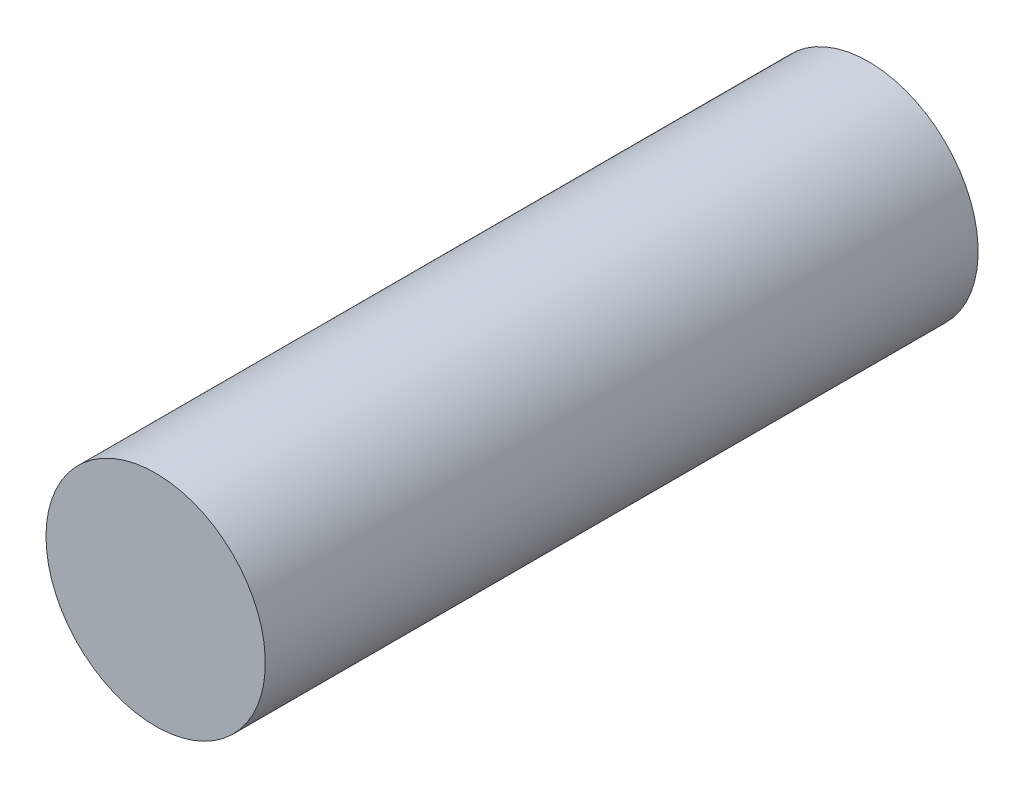
SolidWorks part; units mm, degrees
ref_plane "前视基准面" through (0, 0, 0) normal (0, 0, 1) x (1, 0, 0)
ref_plane "上视基准面" through (0, 0, 0) normal (0, 1, 0) x (1, 0, 0)
ref_plane "右视基准面" through (0, 0, 0) normal (1, 0, 0) x (0, 0, -1)
sketch "草图1" plane through (0, 0, 0) normal (0, 0, 1) x (1, 0, 0)
  circle A0 centre (0, 0) radius 4
  dimension "D1" = 8
extrude "凸台-拉伸1" add sketch "草图1" along normal blind 26
